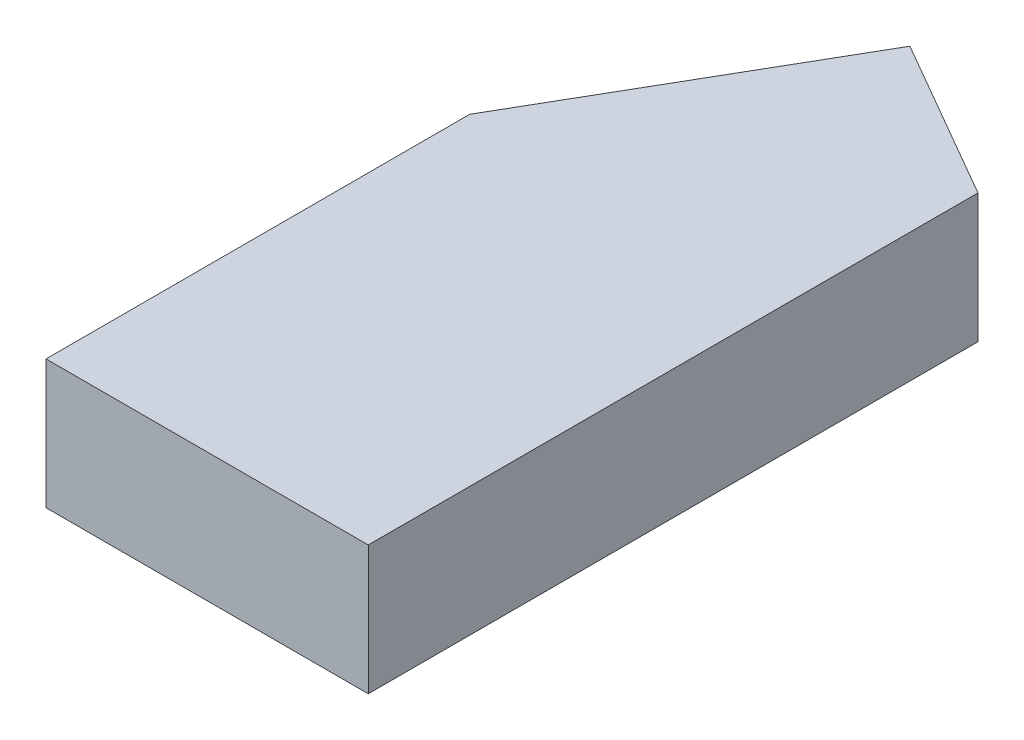
SolidWorks part; units mm, degrees
ref_plane "Front Plane" through (0, 0, 0) normal (0, 0, 1) x (1, 0, 0)
ref_plane "Top Plane" through (0, 0, 0) normal (0, 1, 0) x (1, 0, 0)
ref_plane "Right Plane" through (0, 0, 0) normal (1, 0, 0) x (0, 0, -1)
sketch "Sketch1" plane through (0, 0, 0) normal (0, 1, 0) x (1, 0, 0)
  line L6 (34.9615, 20.185) -> (0, 40.3701) construction
  line L11 (59.9615, -12.685) -> (59.9615, 34.6188)
  line L12 (59.9615, 34.6188) -> (0, 69.2376) construction
  line L17 (59.9615, -34.6188) -> (59.9615, 34.6188) construction
  line L22 (34.9615, -20.185) -> (34.9615, 20.185) construction
  line L36 (59.9615, -12.685) -> (34.9615, -12.685)
  line L40 (34.9615, -12.685) -> (34.9615, 20.185)
  line L58 (59.9615, 34.6188) -> (47.4615, 41.8357)
  line L63 (34.9615, 20.185) -> (47.4615, 41.8357)
  line L99 (-34.9615, 20.185) -> (-34.9615, -20.185) construction
  line L100 (-34.9615, -20.185) -> (0, -40.3701) construction
  line L101 (0, -40.3701) -> (34.9615, -20.185) construction
  line L106 (-59.9615, 34.6188) -> (-59.9615, -34.6188) construction
  line L107 (-59.9615, -34.6188) -> (0, -69.2376) construction
  line L108 (0, -69.2376) -> (59.9615, -34.6188) construction
  line L110 (0, 69.2376) -> (-59.9615, 34.6188) construction
  line L112 (0, 40.3701) -> (-34.9615, 20.185) construction
  point P0 (26.8111, 6.0633)
extrude "Boss-Extrude1" add sketch "Sketch1" along normal blind 10
